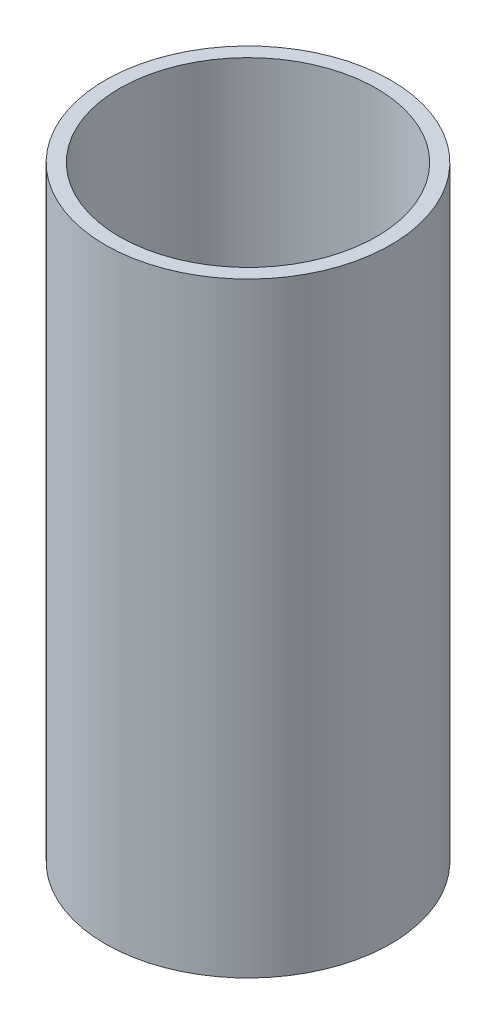
SolidWorks part; units mm, degrees
material "Cam"
ref_plane "Ön Düzlem" through (0, 0, 0) normal (0, 0, 1) x (1, 0, 0)
ref_plane "Üst Düzlem" through (0, 0, 0) normal (0, 1, 0) x (1, 0, 0)
ref_plane "Sağ Düzlem" through (0, 0, 0) normal (1, 0, 0) x (0, 0, -1)
sketch "Çizim1" plane through (0, 0, 0) normal (0, 1, 0) x (1, 0, 0)
  circle A0 centre (0, 0) radius 50
  circle A1 centre (0, 0) radius 45
  dimension "D1" = 100
  dimension "D2" = 90
extrude "Yükseklik-Ekstrüzyon1" add sketch "Çizim1" along normal mid plane 212
